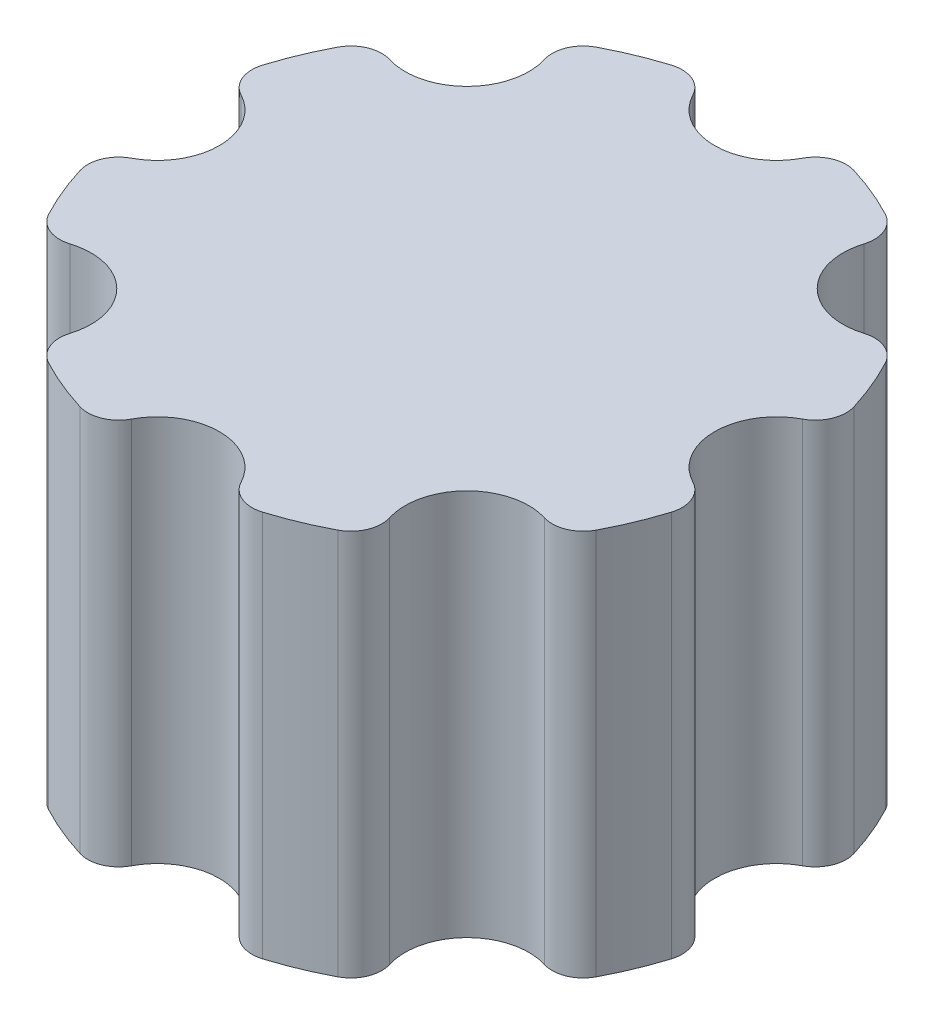
SolidWorks part; units mm, degrees
ref_plane "Front Plane" through (0, 0, 0) normal (0, 0, 1) x (1, 0, 0)
ref_plane "Top Plane" through (0, 0, 0) normal (0, 1, 0) x (1, 0, 0)
ref_plane "Right Plane" through (0, 0, 0) normal (1, 0, 0) x (0, 0, -1)
sketch "Sketch1" plane through (0, 0, 0) normal (0, 1, 0) x (1, 0, 0)
  circle A0 centre (0, 0) radius 20
extrude "Boss-Extrude1" add sketch "Sketch1" along normal blind 25
sketch "Sketch2" plane through (0, 25, 0) normal (0, 1, 0) x (1, 0, 0)
  circle A0 centre (0, 20) radius 4
  circle A1 centre (0, 0) radius 20 construction
  circle A2 centre (14.1421, 14.1421) radius 4
  circle A3 centre (20, 0) radius 4
  circle A4 centre (14.1421, -14.1421) radius 4
  circle A5 centre (0, -20) radius 4
  circle A6 centre (-14.1421, -14.1421) radius 4
  circle A7 centre (-20, 0) radius 4
  circle A8 centre (-14.1421, 14.1421) radius 4
  point P20 (0, 0)
  dimension "D1" = 8
extrude "Cut-Extrude1" cut sketch "Sketch2" against normal blind 25
fillet "Fillet1" radius 2 16 edges at (3.9799, 12.5, 19.6) (-3.9799, 12.5, 19.6) (-11.045, 12.5, 16.6735) (-16.6735, 12.5, 11.045) (-19.6, 12.5, 3.9799) (-19.6, 12.5, -3.9799) (-16.6735, 12.5, -11.045) (-11.045, 12.5, -16.6735) (-3.9799, 12.5, -19.6) (3.9799, 12.5, -19.6) (11.045, 12.5, -16.6735) (16.6735, 12.5, -11.045) (19.6, 12.5, -3.9799) (19.6, 12.5, 3.9799) (16.6735, 12.5, 11.045) (11.045, 12.5, 16.6735)
